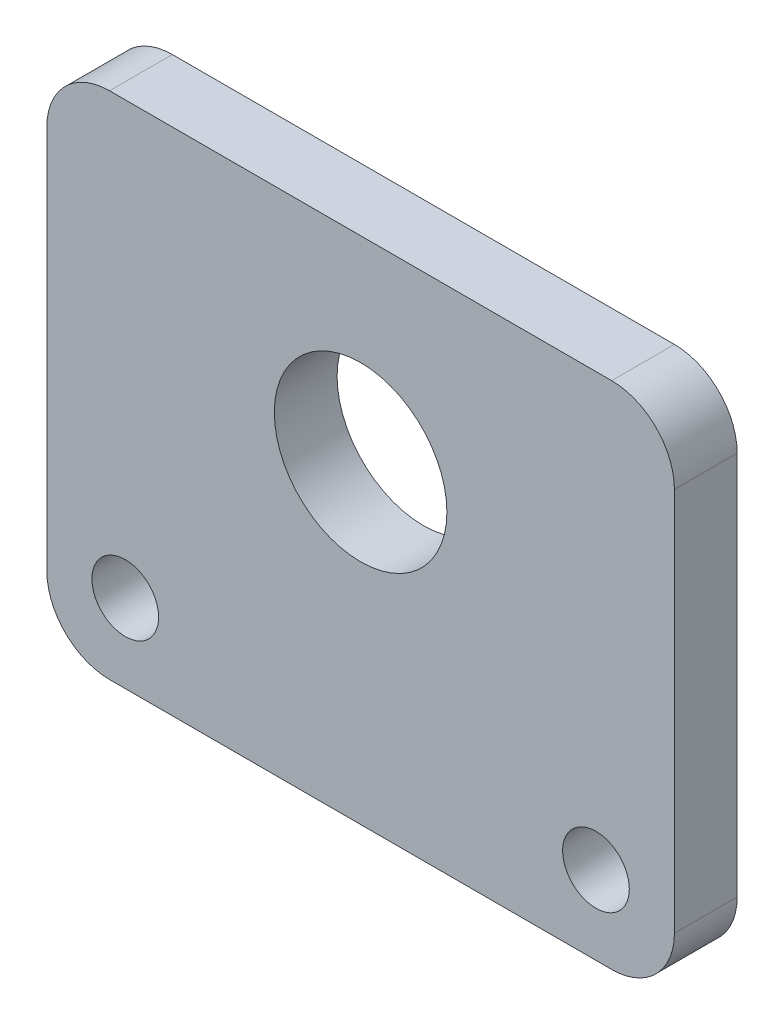
SolidWorks part; units mm, degrees
material "PET"
ref_plane "xy" through (0, 0, 0) normal (0, 0, 1) x (1, 0, 0)
ref_plane "xz" through (0, 0, 0) normal (0, 1, 0) x (1, 0, 0)
ref_plane "yz" through (0, 0, 0) normal (1, 0, 0) x (0, 0, -1)
sketch "Skizze1" plane through (0, 0, 0) normal (0, 0, 1) x (1, 0, 0)
  line L1 (-40, 25) -> (40, 25)
  line L2 (-40, 25) -> (-40, -40)
  line L3 (-40, -40) -> (40, -40)
  line L4 (40, 25) -> (40, -40)
  line L9 (-30, 15) -> (30, 15) construction
  line L10 (-30, 15) -> (-30, -30) construction
  line L11 (-30, -30) -> (30, -30) construction
  line L12 (30, 15) -> (30, -30) construction
  circle A0 centre (0, 0) radius 11
  circle A5 centre (-30, 15) radius 10 construction
  circle A6 centre (-30, 15) radius 4.25 construction
  circle A7 centre (30, 15) radius 4.25 construction
  circle A8 centre (-30, -30) radius 4.25
  circle A9 centre (30, -30) radius 4.25
  point P4 (0, -40)
  point P26 (0, -30)
  dimension "D1" = 22
  dimension "D3" = 65
  dimension "D4" = 10
  dimension "D5" = 8.5
  dimension "D6" = 80
  dimension "D2" = 40
  dimension "D7" = 10
extrude "Aufsatz-Linear austragen1" add sketch "Skizze1" along normal mid plane 8
fillet "Verrundung1" radius 8 4 edges at (40, -40, 0) (-40, -40, 0) (-40, 25, 0) (40, 25, 0)
